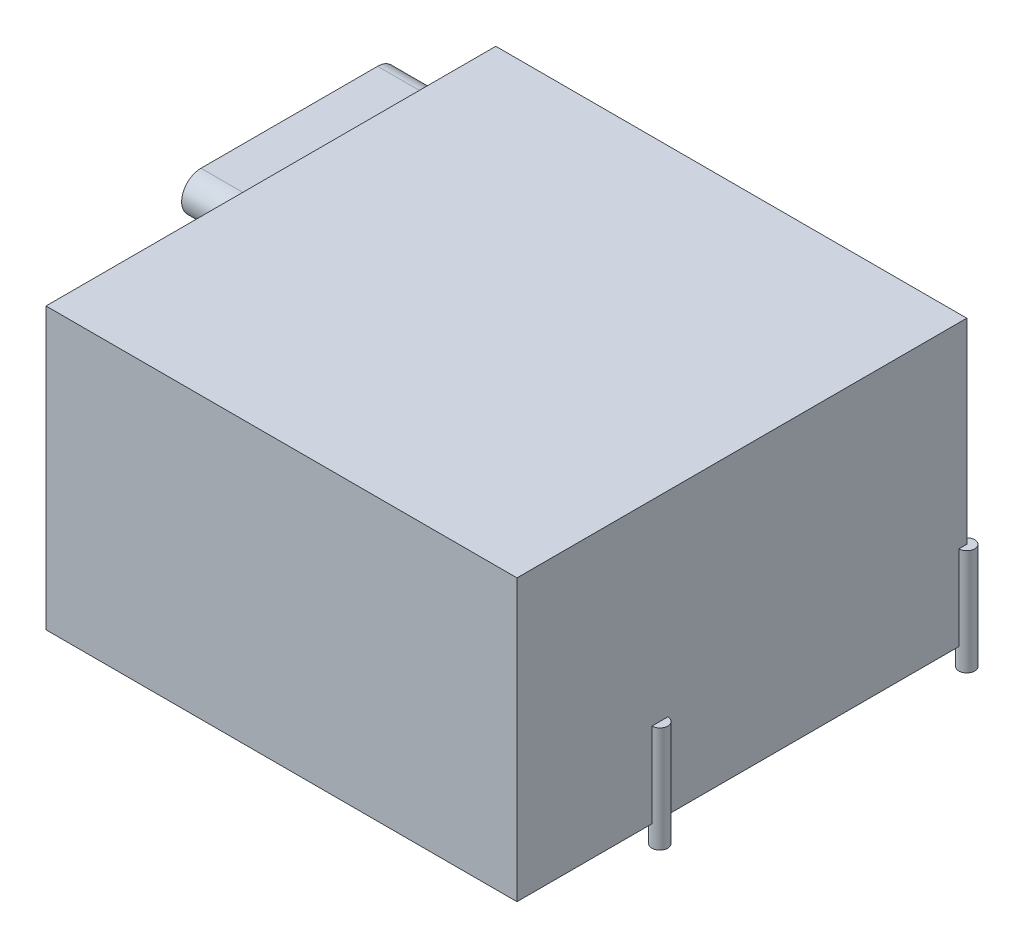
SolidWorks part; units mm, degrees
ref_plane "Front Plane" through (0, 0, 0) normal (0, 0, 1) x (1, 0, 0)
ref_plane "Top Plane" through (0, 0, 0) normal (0, 1, 0) x (1, 0, 0)
ref_plane "Right Plane" through (0, 0, 0) normal (1, 0, 0) x (0, 0, -1)
sketch "Sketch2" plane through (0, 0, 0) normal (0, 1, 0) x (1, 0, 0)
  line L1 (-44.5, -29) -> (44.5, -29)
  line L2 (-44.5, -29) -> (-44.5, 29)
  line L3 (-44.5, 29) -> (44.5, 29)
  line L4 (44.5, -29) -> (44.5, 29)
  line L5 (-44.5, -29) -> (44.5, 29) construction
  line L6 (-44.5, 29) -> (44.5, -29) construction
  circle A0 centre (-44.5, 29) radius 1.5
  circle A1 centre (44.5, 29) radius 1.5
  circle A2 centre (-44.5, -29) radius 1.5
  circle A3 centre (44.5, -29) radius 1.5
  point P0 (0, 0)
  dimension "D3" = 3
  dimension "D4" = 3
  dimension "D5" = 3
  dimension "D6" = 3
  dimension "D1" = 89
  dimension "D2" = 58
extrude "Boss-Extrude1" add sketch "Sketch2" along normal blind 20 contours A2 | A0 | A3 | A1
ref_plane "Plane1" through (0, 20, 0) normal (0, 1, 0) x (1, 0, 0)
sketch "Sketch3" plane through (0, 20, 0) normal (0, 1, 0) x (1, 0, 0)
  line L0 (-44.5, 29) -> (44.5, 29)
  line L5 (-44.5, 29) -> (-44.5, -56)
  line L6 (44.5, 29) -> (44.5, -56)
  line L7 (-44.5, -56) -> (44.5, -56)
  point P0 (0, 0)
  dimension "D1" = 85
extrude "Boss-Extrude2" add sketch "Sketch3" along normal blind 37 and the other way blind 16
sketch "Sketch7" plane through (-44.5, 0, 0) normal (-1, 0, 0) x (0, 0, 1)
  line L0 (-20.6613, 47.2362) -> (12.7112, 47.2362) construction
  line L1 (-20.6613, 50.8952) -> (12.7112, 50.8952)
  line L2 (-20.6613, 43.5772) -> (12.7112, 43.5772)
  arc A0 (-20.6613, 50.8952) -> (-20.6613, 43.5772) centre (-20.6613, 47.2362) ccw
  arc A1 (12.7112, 43.5772) -> (12.7112, 50.8952) centre (12.7112, 47.2362) ccw
  point P2 (-3.975, 47.2362)
extrude "Boss-Extrude5" add sketch "Sketch7" along normal blind 14
sketch "Sketch8" plane through (0, 0, -29) normal (0, 0, -1) x (-1, 0, 0)
  line L0 (-46, 0) -> (-43, 0) construction
  line L1 (-26.8, 23.15) -> (-34.8, 23.15)
  line L2 (-26.8, 23.15) -> (-26.8, 31.15)
  line L3 (-26.8, 31.15) -> (-34.8, 31.15)
  line L4 (-34.8, 23.15) -> (-34.8, 31.15)
  line L5 (-44.5, 20) -> (-44.5, 57) construction
  point P8 (0, 0)
  dimension "D1" = 23.15
  dimension "D2" = 9.7
  dimension "D3" = 8
  dimension "D4" = 8
extrude "Boss-Extrude6" add sketch "Sketch8" along normal blind 5
